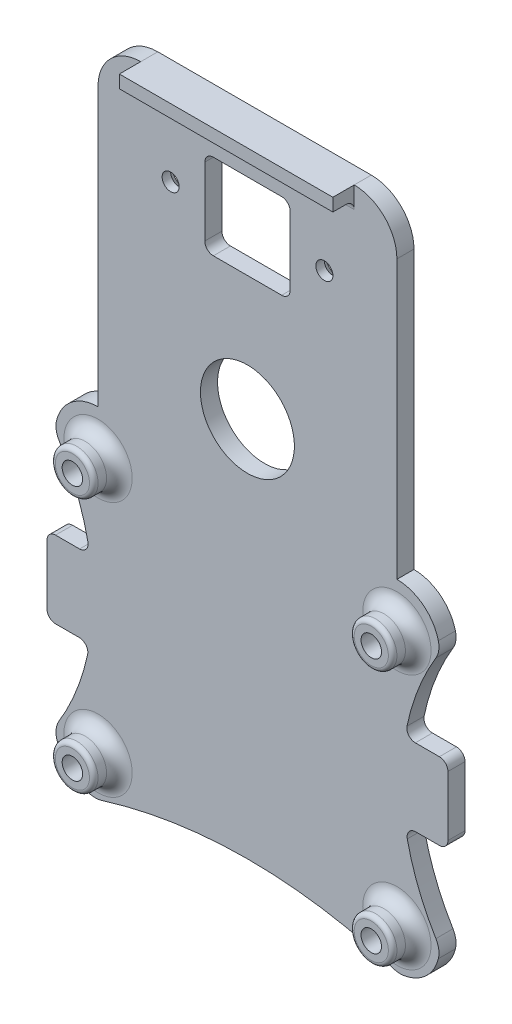
SolidWorks part; units mm, degrees
ref_plane "Front Plane" through (0, 0, 0) normal (0, 0, 1) x (1, 0, 0)
ref_plane "Top Plane" through (0, 0, 0) normal (0, 1, 0) x (1, 0, 0)
ref_plane "Right Plane" through (0, 0, 0) normal (1, 0, 0) x (0, 0, -1)
sketch "Sketch1" plane through (0, 0, 0) normal (0, 0, 1) x (1, 0, 0)
  line L0 (-35, -30.3) -> (35, -30.3) construction
  line L1 (-35, 29.5) -> (35, 29.5) construction
  line L2 (0, 40) -> (0, -55.1813) construction
  line L3 (-35, 40) -> (35, 40)
  line L4 (-39.3198, 9) -> (-44.95, 9)
  line L5 (44.95, -9) -> (39.3857, -9)
  line L6 (46.95, -7) -> (46.95, 7)
  line L7 (44.95, 9) -> (39.3198, 9)
  line L8 (-46.95, -7) -> (-46.95, 7)
  line L13 (-39.3857, -9) -> (-44.95, -9)
  circle A0 centre (-35, 29.5) radius 2.4
  circle A1 centre (35, 29.5) radius 2.4
  circle A2 centre (-35, -30.3) radius 2.4
  circle A3 centre (35, -30.3) radius 2.4
  arc A4 (35, 40) -> (45, 30) centre (35, 30) cw
  arc A5 (45, -29.6893) -> (35.245, -39.6893) centre (35, -29.6923) cw
  arc A6 (-35, -39.6893) -> (-45, -29.6893) centre (-35, -29.6893) cw
  arc A7 (-45, 30) -> (-35, 40) centre (-35, 30) cw
  arc A8 (-45, 30) -> (-37.3621, 11.4092) centre (-91.1985, 0.1554) cw
  arc A9 (45, 30) -> (37.3621, 11.4092) centre (91.1985, 0.1554) ccw
  arc A10 (-35, -39.6893) -> (35.245, -39.6893) centre (0.1225, -149.1946) cw
  circle A11 centre (-35, 29.5) radius 11.95 construction
  arc A12 (-37.4305, -11.421) -> (-45, -29.6893) centre (-91.1985, 0.1554) cw
  arc A13 (37.4305, -11.421) -> (45, -29.6893) centre (91.1985, 0.1554) ccw
  arc A14 (-44.95, 9) -> (-46.95, 7) centre (-44.95, 7) ccw
  arc A15 (-46.95, -7) -> (-44.95, -9) centre (-44.95, -7) ccw
  arc A16 (44.95, -9) -> (46.95, -7) centre (44.95, -7) ccw
  arc A17 (46.95, 7) -> (44.95, 9) centre (44.95, 7) ccw
  arc A18 (39.3198, 9) -> (37.3621, 11.4092) centre (39.3198, 11) cw
  arc A19 (39.3857, -9) -> (37.4305, -11.421) centre (39.3857, -11) ccw
  arc A20 (-37.4305, -11.421) -> (-39.3857, -9) centre (-39.3857, -11) ccw
  arc A21 (-39.3198, 9) -> (-37.3621, 11.4092) centre (-39.3198, 11) ccw
  point P0 (0, 0)
  point P6 (0, 0)
  point P18 (45, 40)
  point P30 (0, 0)
  point P39 (-46.95, 9)
  point P44 (-46.95, -9)
  point P53 (36.9658, -9)
  point P56 (-36.9658, -9)
  dimension "D5" = 10
  dimension "D2" = 23.9
  dimension "D7" = 2
  dimension "D1" = 10.5
  dimension "D3" = 59.8
  dimension "D4" = 70
  dimension "D6" = 18
extrude "Boss-Extrude1" add sketch "Sketch1" along normal blind 4
sketch "Sketch2" plane through (0, 0, 4) normal (0, 0, 1) x (1, 0, 0)
  circle A0 centre (-35, 29.5) radius 5.0046
  circle A1 centre (35, 29.5) radius 5
  circle A2 centre (-35, -30.3) radius 5
  circle A3 centre (35, -30.3) radius 5
  circle A4 centre (-35, 29.5) radius 2.4
  circle A5 centre (35, 29.5) radius 2.4
  circle A6 centre (35, -30.3) radius 2.4
  circle A7 centre (-35, -30.3) radius 2.4
extrude "Boss-Extrude2" add sketch "Sketch2" along normal blind 6
chamfer "Chamfer1" [suppressed] distance 3 angle 45
fillet "Fillet1" radius 3 4 edges at (-40, -30.3, 4) (30, -30.3, 4) (30, 29.5, 4) (-40.0046, 29.5, 4)
fillet "Fillet2" radius 1 4 edges at (-30, -30.3, 10) (40, -30.3, 10) (40, 29.5, 10) (-29.9954, 29.5, 10)
fillet "Fillet3" radius 5 6 edges at (45, 30, 2) (35.245, -39.6893, 2) (-35, -39.6893, 2) (-45, 30, 2) (-45, -29.6893, 2) (45, -29.6893, 2)
sketch "Sketch3" plane through (0, 0, 0) normal (0, 0, -1) x (-1, 0, 0)
  line L0 (-35, 40) -> (35, 40) construction
  line B0 (-35, 40) -> (35, 40)
  line B1 (-35, 40) -> (-35, 105)
  line B2 (-25, 115) -> (25, 115)
  line B3 (35, 40) -> (35, 105)
  arc B4 (35, 105) -> (25, 115) centre (25, 105) ccw
  arc B5 (-25, 115) -> (-35, 105) centre (-25, 105) ccw
sketch_block_instance "Block1-1"
sketch_block "Block1"
extrude "Boss-Extrude3" add sketch "Sketch3" against normal blind 4
sketch "Sketch4" plane through (0, 0, 0) normal (0, 0, -1) x (-1, 0, 0)
  line L0 (0, 115) -> (-0.0863, -34.1946) construction
  line L1 (25, 115) -> (-25, 115) construction
  arc A0 (34.1514, -39.4207) -> (-34.3274, -39.3992) centre (-0.1225, -149.1946) ccw construction
  circle A1 centre (-18.0121, 94.13) radius 2
  circle A2 centre (17.9879, 94.13) radius 2
  line B0 (-8.0121, 84.13) -> (7.9879, 84.13)
  line B1 (-10.0121, 86.13) -> (-10.0121, 102.13)
  line B2 (-8.0121, 104.13) -> (7.9879, 104.13)
  line B3 (9.9879, 86.13) -> (9.9879, 102.13)
  line B4 (-10.0121, 84.13) -> (9.9879, 104.13) construction
  line B5 (-10.0121, 104.13) -> (9.9879, 84.13) construction
  arc B6 (-10.0121, 86.13) -> (-8.0121, 84.13) centre (-8.0121, 86.13) ccw
  arc B7 (7.9879, 84.13) -> (9.9879, 86.13) centre (7.9879, 86.13) ccw
  arc B8 (9.9879, 102.13) -> (7.9879, 104.13) centre (7.9879, 102.13) ccw
  arc B9 (-8.0121, 104.13) -> (-10.0121, 102.13) centre (-8.0121, 102.13) ccw
  circle B10 centre (0.0106, 54.9994) radius 11
  dimension "D2" = 18
  dimension "D1" = 10.87
  dimension "D3" = 18
sketch_block_instance "Block2-1"
sketch_block "Block2" parameters "D2"=2, "D1"=20
extrude "Cut-Extrude1" cut sketch "Sketch4" against normal up to next
chamfer "Chamfer2" distance 2 angle 45 2 edges at (16.0121, 94.13, 0) (-19.9879, 94.13, 0)
sketch "Sketch5" plane through (0, 0, 4) normal (0, 0, 1) x (1, 0, 0)
  line L1 (-25, 115) -> (25, 115)
  line L2 (-25, 115) -> (-25, 112)
  line L3 (-25, 112) -> (25, 112)
  line L4 (25, 115) -> (25, 112)
  dimension "D1" = 3
extrude "Boss-Extrude4" add sketch "Sketch5" along normal blind 5
fillet "Fillet4" radius 2 1 edges at (0, 112, 4)
